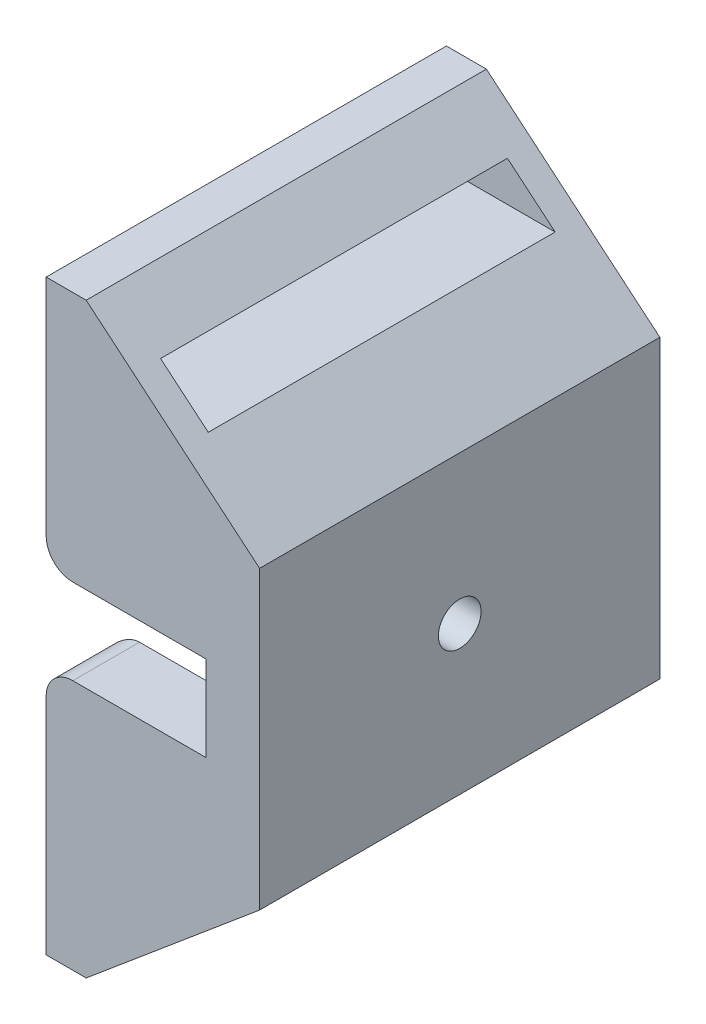
SolidWorks part; units mm, degrees
ref_plane "Front Plane" through (0, 0, 0) normal (0, 0, 1) x (1, 0, 0)
ref_plane "Top Plane" through (0, 0, 0) normal (0, 1, 0) x (1, 0, 0)
ref_plane "Right Plane" through (0, 0, 0) normal (1, 0, 0) x (0, 0, -1)
sketch "Sketch1" plane through (0, 0, -7.5) normal (-1, 0, 0) x (0, 0, 1)
  line L5 (-7.5, -11) -> (7.5, -11)
  line L6 (-7.5, -11) -> (-7.5, 11)
  line L7 (-7.5, 11) -> (7.5, 11)
  line L8 (7.5, -11) -> (7.5, 11)
  line L9 (-7.5, -11) -> (7.5, 11) construction
  line L10 (-7.5, 11) -> (7.5, -11) construction
  point P0 (0, 0)
  point P5 (0, 0)
  point P6 (0, 0)
  point P7 (0, 0)
  point P8 (0, 0)
  point P9 (0, 0)
  point P10 (0, 0)
  point P11 (0, 0)
  point P12 (0, 0)
  point P13 (0, 0)
  point P14 (0, 0)
  point P15 (0, 0)
  point P16 (0, 0)
  point P17 (7.5, 0)
  point P18 (0, 0)
  point P19 (0, 0)
  dimension "D1" = 15
  dimension "D2" = 22
extrude "Boss-Extrude1" add sketch "Sketch1" along normal blind 8
sketch "Sketch2" plane through (-8, 0, 0) normal (-1, 0, 0) x (0, 0, 1)
  circle A0 centre (-7.5, 0) radius 5.25
  point P3 (0, 0)
  point P4 (-6.8854, 0)
  point P5 (0, 0)
  point P6 (0, 0)
  point P7 (0, 0)
  dimension "D1" = 10.5
extrude "Cut-Extrude1" cut sketch "Sketch2" against normal blind 6
sketch "Sketch3" plane through (5, 0, 0) normal (0, 0, 1) x (1, 0, 0)
  line L16 (-13, 1.6) -> (-7, 1.6)
  line L17 (-13, 1.6) -> (-13, -1.6)
  line L22 (-13, -1.6) -> (-7, -1.6)
  line L23 (-7, 1.6) -> (-7, -1.6)
  point P4 (0, 0)
  point P5 (0, 0)
  point P6 (0, 0)
  point P7 (0, 0)
  point P8 (0, 0)
  point P9 (0, 0)
  point P10 (0, 0)
extrude "Cut-Extrude2" cut sketch "Sketch3" against normal up to next
sketch "Sketch4" plane through (0, 0, 0) normal (1, 0, 0) x (0, 0, -1)
  line L0 (0, -11) -> (0, 11) construction
  line L9 (15, 11) -> (15, -11) construction
  line L12 (1, 9.5) -> (14, 9.5)
  line L13 (1, 9.5) -> (1, 8)
  line L14 (1, 8) -> (14, 8)
  line L15 (14, 9.5) -> (14, 8)
  line L16 (1, -9.5) -> (14, -9.5)
  line L17 (1, -9.5) -> (1, -8)
  line L18 (1, -8) -> (14, -8)
  line L19 (14, -9.5) -> (14, -8)
  point P4 (0, 0)
  point P5 (0, 0)
  point P6 (0, 0)
  point P11 (14, -8.75)
  point P12 (0, 0)
  point P13 (0, 0)
  point P14 (0, 0)
  point P15 (0, 0)
  dimension "D1" = 13
  dimension "D2" = 13
  dimension "D3" = 1.5
  dimension "D4" = 1.5
  dimension "D5" = 1
  dimension "D6" = 1
  dimension "D7" = 1
  dimension "D8" = 1
extrude "Cut-Extrude3" cut sketch "Sketch4" against normal blind 10
sketch "Sketch5" plane through (-2, 0, 0) normal (-1, 0, 0) x (0, 0, 1)
  circle A0 centre (-7.5, 0) radius 0.8
  point P3 (0, 0)
  dimension "D1" = 1.6
extrude "Cut-Extrude4" cut sketch "Sketch5" against normal through all
sketch "Sketch6" plane through (0, 0, 0) normal (0, 0, 1) x (1, 0, 0)
  line L0 (0, -11) -> (-6.5, -11)
  line L1 (-8, -11) -> (0, -11) construction
  line L2 (-6.5, -11) -> (0, -5.5459)
  line L3 (-8, -11) -> (-8, -1.6) construction
  line L4 (0, -11) -> (0, -5.5459)
  line L5 (0, -11) -> (0, 11) construction
  line L7 (0, 11) -> (-6.5, 11)
  line L8 (-8, 11) -> (0, 11) construction
  line L9 (-6.5, 11) -> (0, 5.5459)
  line L10 (-8, 1.6) -> (-8, 11) construction
  line L13 (0, 5.5459) -> (0, 11)
  dimension "D1" = 1.5
  dimension "D2" = 40
  dimension "D3" = 1.5
  dimension "D4" = 40
extrude "Cut-Extrude5" cut sketch "Sketch6" against normal through all
fillet "Fillet1" radius 1 3 edges at (-8, 0, -12.75) (-8, 1.6, -1.2499) (-8, -1.6, -1.2499)
